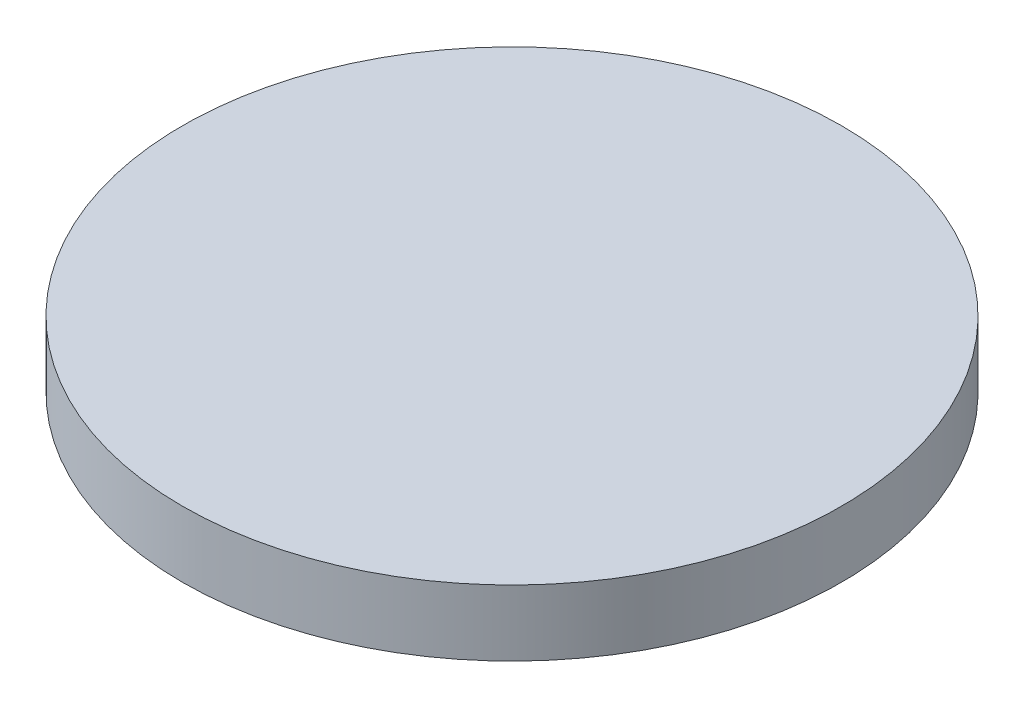
SolidWorks part; units mm, degrees
ref_plane "Front Plane" through (0, 0, 0) normal (0, 0, 1) x (1, 0, 0)
ref_plane "Top Plane" through (0, 0, 0) normal (0, 1, 0) x (1, 0, 0)
ref_plane "Right Plane" through (0, 0, 0) normal (1, 0, 0) x (0, 0, -1)
sketch "Sketch1" plane through (0, 0, 0) normal (0, 1, 0) x (1, 0, 0)
  circle A0 centre (0, 0) radius 40
  point P2 (0, 0)
  dimension "D1" = 80
extrude "Boss-Extrude1" add sketch "Sketch1" along normal blind 8
